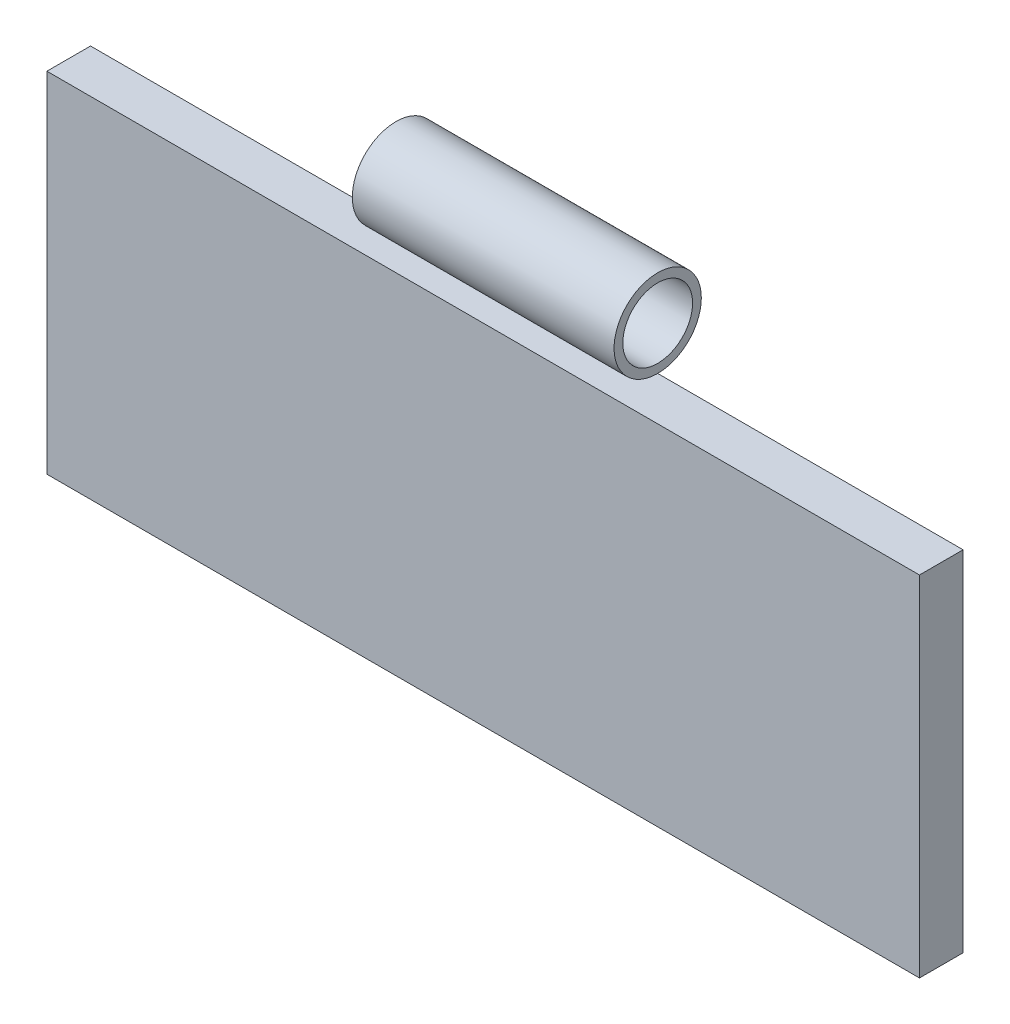
SolidWorks part; units mm, degrees
ref_plane "Front Plane" through (0, 0, 0) normal (0, 0, 1) x (1, 0, 0)
ref_plane "Top Plane" through (0, 0, 0) normal (0, 1, 0) x (1, 0, 0)
ref_plane "Right Plane" through (0, 0, 0) normal (1, 0, 0) x (0, 0, -1)
sketch "Sketch1" plane through (0, 0, 0) normal (0, 0, 1) x (1, 0, 0)
  line L1 (-50, 20) -> (50, 20)
  line L2 (-50, 20) -> (-50, -20)
  line L3 (-50, -20) -> (50, -20)
  line L4 (50, 20) -> (50, -20)
  line L5 (-50, 20) -> (50, -20) construction
  line L6 (-50, -20) -> (50, 20) construction
  point P0 (0, 0)
  dimension "D1" = 100
  dimension "D2" = 40
extrude "Boss-Extrude1" add sketch "Sketch1" along normal blind 5
sketch "Sketch2" plane through (0, 0, 0) normal (0, 0, -1) x (-1, 0, 0)
  line L0 (0, 0) -> (0, 25) construction
  line L2 (-15, 25) -> (15, 25)
  dimension "D1" = 25
  dimension "D2" = 15
revolve "Revolve-Thin1" add sketch "Sketch2" angle 360 about L2 wall 5
sketch "Sketch3" plane through (-15, 0, 0) normal (-1, 0, 0) x (0, 0, 1)
  circle A0 centre (0, 25) radius 4
  circle A2 centre (0, 25) radius 5 construction
  dimension "D1" = 8
extrude "Cut-Extrude1" cut sketch "Sketch3" against normal up to next (30 mm away)
